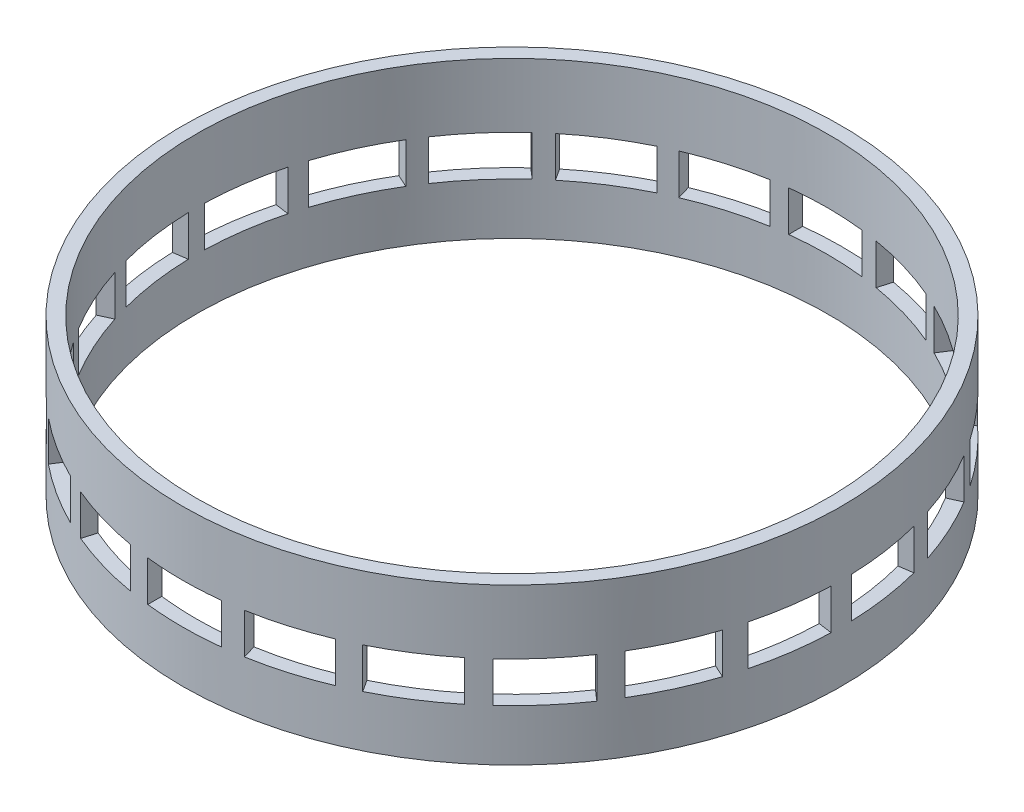
SolidWorks part; units mm, degrees
ref_plane "Front" through (0, 0, 0) normal (0, 0, 1) x (1, 0, 0)
ref_plane "Top" through (0, 0, 0) normal (0, 1, 0) x (1, 0, 0)
ref_plane "Right" through (0, 0, 0) normal (1, 0, 0) x (0, 0, -1)
sketch "Sketch1" plane through (0, 0, 0) normal (0, 1, 0) x (1, 0, 0)
  circle A0 centre (0, 0) radius 85.865
  circle A1 centre (0, 0) radius 89.6625
  dimension "D1" = 179.325
  dimension "D2" = 171.73
extrude "Boss-Extrude1" add sketch "Sketch1" along normal blind 42.425
sketch "Sketch2" plane through (0, 0, 0) normal (0, 0, 1) x (1, 0, 0)
  line L1 (-10, 25) -> (10, 25)
  line L2 (-10, 25) -> (-10, 14)
  line L3 (-10, 14) -> (10, 14)
  line L4 (10, 25) -> (10, 14)
  line L5 (-89.6625, 0) -> (89.6625, 0) construction
  line L6 (-85.865, 0) -> (85.865, 0) construction
  line L7 (0, 0) -> (0, 25) construction
  dimension "D1" = 14
  dimension "D2" = 11
  dimension "D3" = 20
extrude "Cut-Extrude1" cut sketch "Sketch2" against normal through all both and the other way through all
pattern_circular "CirPattern1" count 11 over 360 about axis through (0, 0, 0) along (0, 1, 0) of "Cut-Extrude1"
